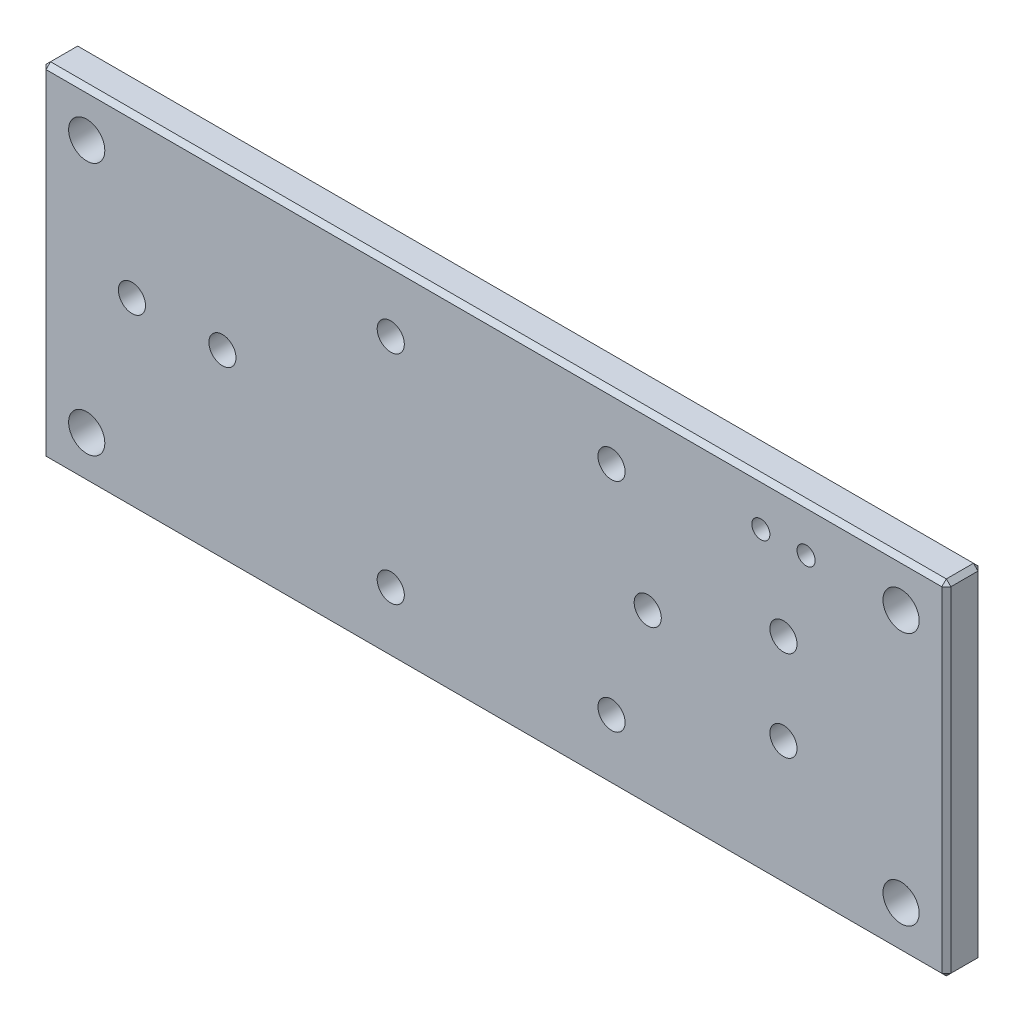
SolidWorks part; units mm, degrees
ref_plane "Спереди" through (0, 0, 0) normal (0, 0, 1) x (1, 0, 0)
ref_plane "Сверху" through (0, 0, 0) normal (0, 1, 0) x (1, 0, 0)
ref_plane "Справа" through (0, 0, 0) normal (1, 0, 0) x (0, 0, -1)
sketch "Эскиз1" plane through (0, 0, 0) normal (0, 0, 1) x (1, 0, 0)
  line L1 (-25, -9.5) -> (25, -9.5)
  line L2 (-25, -9.5) -> (-25, 9.5)
  line L3 (-25, 9.5) -> (25, 9.5)
  line L4 (25, -9.5) -> (25, 9.5)
  line L5 (-25, -9.5) -> (25, 9.5) construction
  line L6 (-25, 9.5) -> (25, -9.5) construction
  line L7 (-22.5, -7) -> (22.5, -7) construction
  line L8 (-22.5, -7) -> (-22.5, 7) construction
  line L9 (-22.5, 7) -> (22.5, 7) construction
  line L10 (22.5, -7) -> (22.5, 7) construction
  line L11 (-22.5, -7) -> (22.5, 7) construction
  line L12 (-22.5, 7) -> (22.5, -7) construction
  circle A0 centre (-22.5, 7) radius 1
  circle A1 centre (22.5, 7) radius 1
  circle A2 centre (22.5, -7) radius 1
  circle A3 centre (-22.5, -7) radius 1
  point P0 (0, 0)
  point P6 (0, 0)
  dimension "D3" = 2
  dimension "D1" = 50
  dimension "D2" = 19
  dimension "D4" = 45
  dimension "D5" = 14
extrude "Бобышка-Вытянуть1" add sketch "Эскиз1" along normal blind 2
sketch "Эскиз2" plane through (0, 0, 2) normal (0, 0, 1) x (1, 0, 0)
  line L0 (-16.5115, 0) -> (20.4763, 0) construction
  line L1 (-5.7, -6) -> (-5.7, 6) construction
  line L2 (25, -9.5) -> (25, 9.5) construction
  line L3 (16, -2.5) -> (16, 2.5) construction
  line L4 (-25, 9.5) -> (-25, -9.5) construction
  line L5 (-20, 0.7) -> (-15, 0.7) construction
  line L6 (25, 9.5) -> (-25, 9.5) construction
  line L7 (14.75, 7) -> (17.25, 7) construction
  circle A0 centre (-5.7, 6) radius 0.75
  circle A1 centre (-5.7, -6) radius 0.75
  circle A2 centre (6.5, 6) radius 0.75
  circle A3 centre (6.5, -6) radius 0.75
  circle A4 centre (8.5, 0) radius 0.75
  circle A5 centre (16, 2.5) radius 0.75
  circle A6 centre (16, -2.5) radius 0.75
  circle A7 centre (14.75, 7) radius 0.5
  circle A8 centre (-20, 0.7) radius 0.75
  circle A9 centre (-15, 0.7) radius 0.75
  circle A10 centre (17.25, 7) radius 0.5
  point P10 (-5.7, 0)
  point P19 (16, 0)
  point P33 (16, 7)
  dimension "D5" = 1.5
  dimension "D9" = 2.5
  dimension "D13" = 1
  dimension "D1" = 12
  dimension "D2" = 12.2
  dimension "D3" = 2
  dimension "D4" = 19.3
  dimension "D6" = 9
  dimension "D7" = 5
  dimension "D8" = 4.5
  dimension "D10" = 8.8
  dimension "D11" = 5
  dimension "D12" = 5
extrude "Вырез-Вытянуть1" cut sketch "Эскиз2" against normal blind 2
chamfer "Фаска1" distance 0.25 angle 45 12 edges at (-25, -9.5, 1) (-25, 0, 0) (-25, 0, 2) (-25, 9.5, 1) (0, 9.5, 0) (0, 9.5, 2) (25, 9.5, 1) (25, 0, 0) (0, -9.5, 0) (25, -9.5, 1) (25, 0, 2) (0, -9.5, 2)
